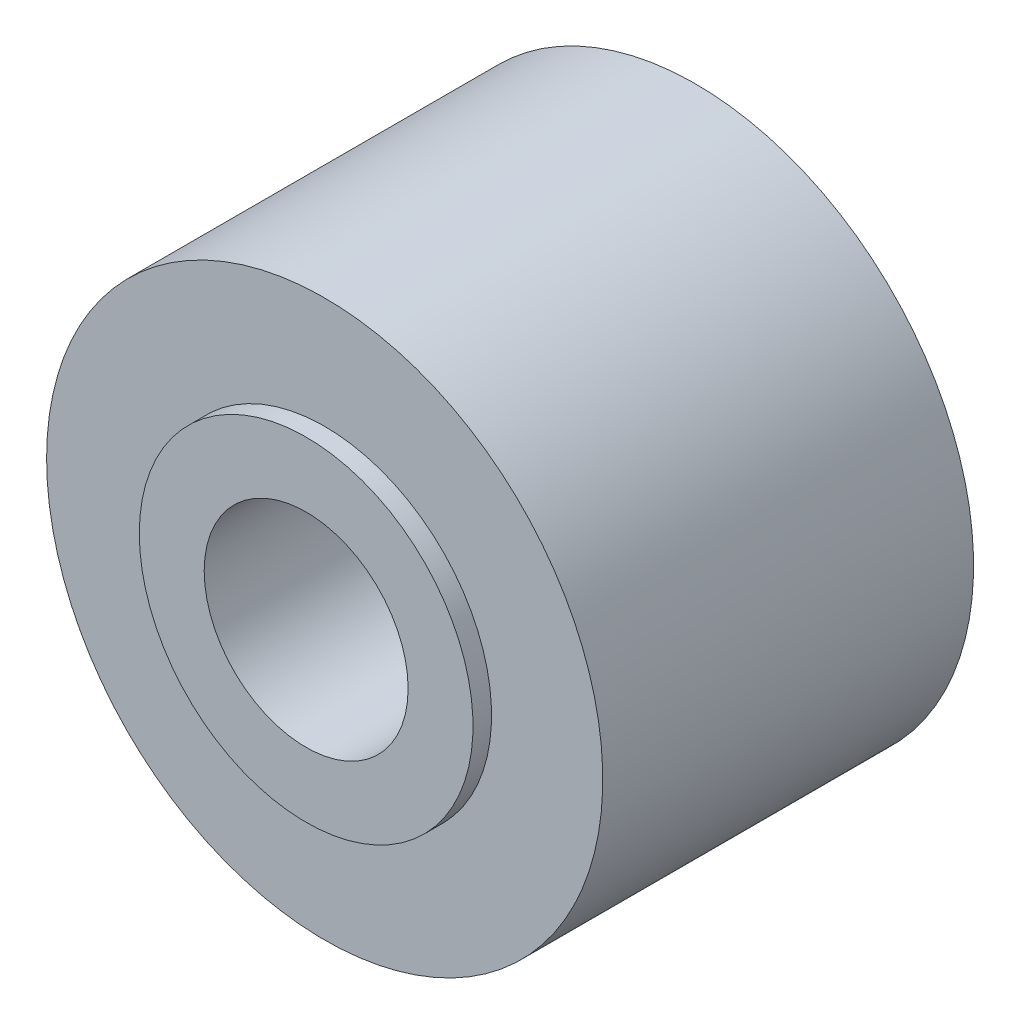
SolidWorks part; units mm, degrees
ref_plane "Frontal Plane" through (0, 0, 0) normal (0, 0, 1) x (1, 0, 0)
ref_plane "Horizontal Plane" through (0, 0, 0) normal (0, 1, 0) x (1, 0, 0)
ref_plane "Profile Plane" through (0, 0, 0) normal (1, 0, 0) x (0, 0, -1)
sketch "Sketch1" plane through (0, 0, 0) normal (1, 0, 0) x (0, 0, -1)
  line L1 (0, -11) -> (0, -30)
  line L2 (0, -30) -> (-40, -30)
  line L3 (-40, -30) -> (-40, -18)
  line L4 (-40, -18) -> (-42, -18)
  line L5 (-42, -18) -> (-42, -11)
  line L8 (74.7869, 0) -> (-74.7869, 0) construction
  line L9 (-42, -11) -> (0, -11)
  point P3 (0, -11)
  point P13 (0, 0)
  dimension "D1" = 11
  dimension "D2" = 30
  dimension "D3" = 2
  dimension "D4" = 18
  dimension "D7" = 40
revolve "Revolve1" add sketch "Sketch1" angle 360 about L8
